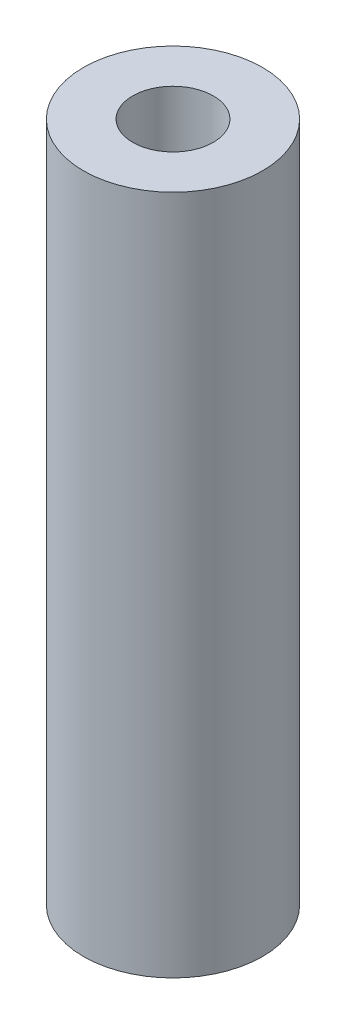
SolidWorks part; units mm, degrees
material "6061-T6 (SS)"
ref_plane "Alzado" through (0, 0, 0) normal (0, 0, 1) x (1, 0, 0)
ref_plane "Planta" through (0, 0, 0) normal (0, 1, 0) x (1, 0, 0)
ref_plane "Vista lateral" through (0, 0, 0) normal (1, 0, 0) x (0, 0, -1)
sketch "Croquis1" plane through (0, 0, 0) normal (0, 1, 0) x (1, 0, 0)
  circle A0 centre (0, 0) radius 5
  dimension "D1" = 10
extrude "Saliente-Extruir1" add sketch "Croquis1" along normal mid plane 38
hole_wizard "Taladro de margen para M41" positions "Croquis2" profile "Croquis3" hole size "M4" standard "Ansi Metric" end condition through all
sketch "Croquis2" plane through (0, 19, 0) normal (0, 1, 0) x (1, 0, 0)
  point P0 (0, 0)
sketch "Croquis3" plane through (0, 19, 0) normal (1, 0, 0) x (0, 0, 1)
  line L0 (0, 0) -> (0, 38)
  line L1 (0, 38) -> (2.25, 38)
  line L2 (2.25, 38) -> (2.25, 0)
  line L5 (2.25, 0) -> (0, 0)
  line L11 (0, -6.35) -> (0, 107.95) construction
  dimension "Diámetro de taladro hasta el siguiente" = 4.5
  dimension "Profundidad de taladro hasta el siguiente" = 38
